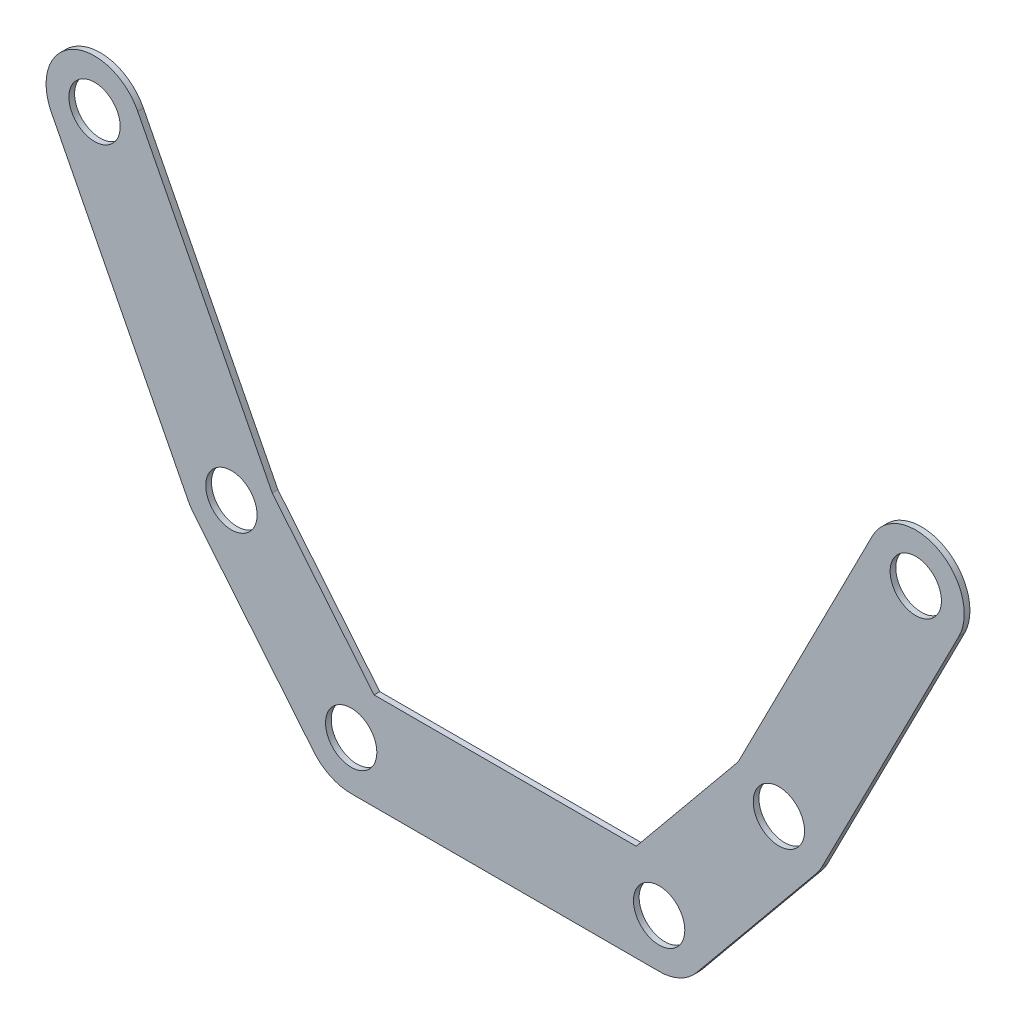
SolidWorks part; units mm, degrees
ref_plane "Front Plane" through (0, 0, 0) normal (0, 0, 1) x (1, 0, 0)
ref_plane "Top Plane" through (0, 0, 0) normal (0, 1, 0) x (1, 0, 0)
ref_plane "Right Plane" through (0, 0, 0) normal (1, 0, 0) x (0, 0, -1)
sketch "Sketch1" plane through (0, 0, 0) normal (0, 0, 1) x (1, 0, 0)
  line L0 (-85.725, 0) -> (85.725, 0) construction
  line L1 (-152.4, 81.1151) -> (-85.725, 0) construction
  line L6 (152.4, 81.1151) -> (85.725, 0) construction
  line L7 (-228.6, 230.2792) -> (228.6, 230.2792) construction
  line L8 (-152.4, 81.1151) -> (152.4, 81.1151) construction
  line L9 (-228.6, 230.2792) -> (-152.4, 81.1151) construction
  line L10 (228.6, 230.2792) -> (152.4, 81.1151) construction
  circle A0 centre (-85.725, 0) radius 38.1
  circle A1 centre (85.725, 0) radius 38.1
  circle A2 centre (-152.4, 81.1151) radius 63.5
  circle A3 centre (152.4, 81.1151) radius 63.5
  circle A4 centre (-228.6, 230.2792) radius 50.8
  circle A5 centre (228.6, 230.2792) radius 50.8
  point P4 (0, 0)
  point P15 (0, 81.1151)
  point P16 (0, 230.2792)
  point P17 (453.3168, 380.2185)
  dimension "D1" = 101.6
  dimension "D2" = 171.45
  dimension "D3" = 127
  dimension "D4" = 457.2
  dimension "D7" = 167.5003
  dimension "D8" = 76.2
  dimension "D5" = 304.8
  dimension "D6" = 105.0011
sketch "Sketch2" plane through (0, 0, 0) normal (0, 0, 1) x (1, 0, 0)
  line L0 (-252.6332, 218.0019) -> (-176.4332, 68.8379)
  line L1 (-173.2483, 63.9783) -> (-106.5733, -17.1369)
  line L2 (-85.725, -26.9875) -> (85.725, -26.9875)
  line L3 (106.5733, -17.1369) -> (173.2483, 63.9783)
  line L4 (176.4332, 68.8379) -> (252.6332, 218.0019)
  line L5 (-72.9737, 26.9875) -> (72.9737, 26.9875)
  line L6 (-204.5668, 242.5565) -> (-129.6962, 95.9947)
  line L7 (-129.6962, 95.9947) -> (-72.9737, 26.9875)
  line L8 (204.5668, 242.5565) -> (129.6962, 95.9947)
  line L9 (72.9737, 26.9875) -> (129.6962, 95.9947)
  line L10 (-131.5517, 98.252) -> (-129.6962, 95.9947) construction
  line L11 (-129.6962, 95.9947) -> (-128.3668, 93.3924) construction
  line L12 (-85.725, 26.9875) -> (-72.9737, 26.9875) construction
  line L13 (-72.9737, 26.9875) -> (-64.8767, 17.1369) construction
  line L14 (64.8767, 17.1369) -> (72.9737, 26.9875) construction
  line L15 (72.9737, 26.9875) -> (85.725, 26.9875) construction
  line L16 (129.6962, 95.9947) -> (128.3668, 93.3924) construction
  line L17 (129.6962, 95.9947) -> (131.5517, 98.252) construction
  circle A0 centre (-228.6, 230.2792) radius 14.2875
  circle A1 centre (-152.4, 81.1151) radius 14.2875
  circle A2 centre (-85.725, 0) radius 14.2875
  circle A3 centre (85.725, 0) radius 14.2875
  circle A4 centre (152.4, 81.1151) radius 14.2875
  circle A5 centre (228.6, 230.2792) radius 14.2875
  arc A6 (-204.5668, 242.5565) -> (-252.6332, 218.0019) centre (-228.6, 230.2792) ccw
  arc A7 (-176.4332, 68.8379) -> (-173.2483, 63.9783) centre (-152.4, 81.1151) ccw
  arc A8 (-106.5733, -17.1369) -> (-85.725, -26.9875) centre (-85.725, 0) ccw
  arc A9 (85.725, -26.9875) -> (106.5733, -17.1369) centre (85.725, 0) ccw
  arc A10 (173.2483, 63.9783) -> (176.4332, 68.8379) centre (152.4, 81.1151) ccw
  arc A11 (252.6332, 218.0019) -> (204.5668, 242.5565) centre (228.6, 230.2792) ccw
  circle A14 centre (-228.6, 230.2792) radius 26.9875 construction
  circle A15 centre (-152.4, 81.1151) radius 26.9875 construction
  arc A16 (-173.2483, 63.9783) -> (-128.3668, 93.3924) centre (-152.4, 81.1151) ccw construction
  arc A17 (-128.3668, 93.3924) -> (-131.5517, 98.252) centre (-152.4, 81.1151) ccw construction
  arc A18 (-85.725, 26.9875) -> (-106.5733, -17.1369) centre (-85.725, 0) ccw construction
  circle A19 centre (-85.725, 0) radius 26.9875 construction
  arc A20 (-85.725, -26.9875) -> (-64.8767, 17.1369) centre (-85.725, 0) ccw construction
  arc A21 (-64.8767, 17.1369) -> (-85.725, 26.9875) centre (-85.725, 0) ccw construction
  arc A22 (85.725, 26.9875) -> (64.8767, 17.1369) centre (85.725, 0) ccw construction
  circle A23 centre (85.725, 0) radius 26.9875 construction
  arc A24 (64.8767, 17.1369) -> (85.725, -26.9875) centre (85.725, 0) ccw construction
  arc A25 (106.5733, -17.1369) -> (85.725, 26.9875) centre (85.725, 0) ccw construction
  arc A26 (128.3668, 93.3924) -> (173.2483, 63.9783) centre (152.4, 81.1151) ccw construction
  circle A27 centre (152.4, 81.1151) radius 26.9875 construction
  arc A28 (176.4332, 68.8379) -> (131.5517, 98.252) centre (152.4, 81.1151) ccw construction
  arc A29 (131.5517, 98.252) -> (128.3668, 93.3924) centre (152.4, 81.1151) ccw construction
  arc A30 (204.5668, 242.5565) -> (252.6332, 218.0019) centre (228.6, 230.2792) ccw construction
  circle A31 centre (228.6, 230.2792) radius 26.9875 construction
  point P27 (-166.6161, 464.4043)
  point P52 (192.6402, 349.0358)
  point P62 (358.8187, 22.0588)
  dimension "D1" = 28.575
  dimension "D2" = 12.7
extrude "Boss-Extrude1" add sketch "Sketch2" along normal blind 3.175
